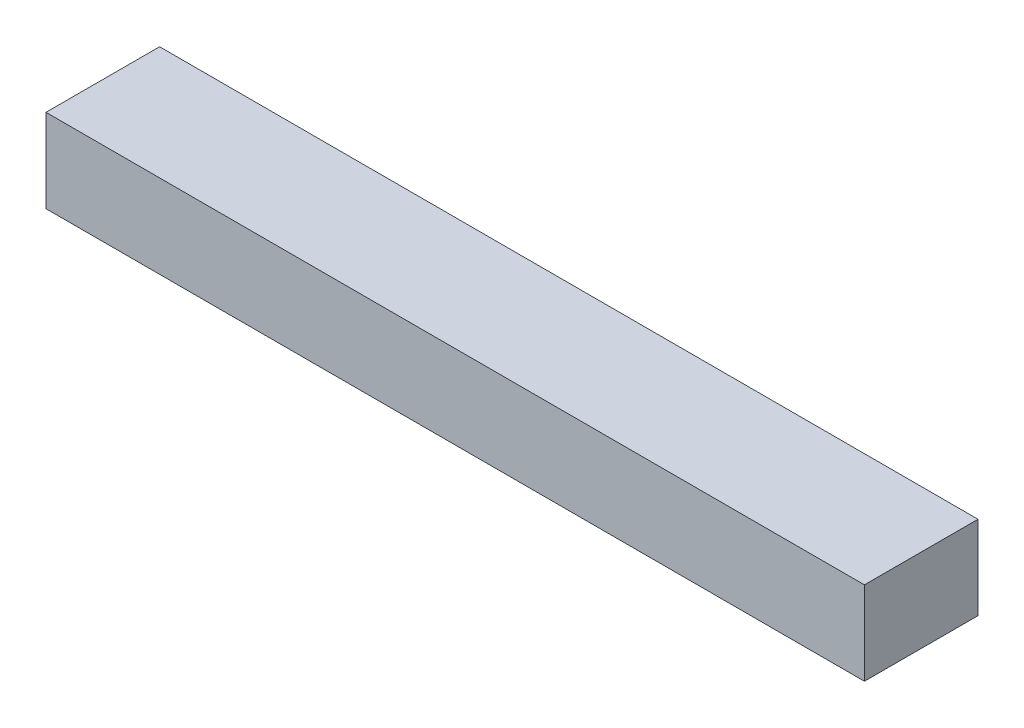
SolidWorks part; units mm, degrees
ref_plane "Front Plane" through (0, 0, 0) normal (0, 0, 1) x (1, 0, 0)
ref_plane "Top Plane" through (0, 0, 0) normal (0, 1, 0) x (1, 0, 0)
ref_plane "Right Plane" through (0, 0, 0) normal (1, 0, 0) x (0, 0, -1)
sketch "Sketch1" plane through (0, 0, 0) normal (0, 1, 0) x (1, 0, 0)
  line L1 (-23.6768, 6.5133) -> (-72.6768, 6.5133)
  line L2 (-23.6768, 6.5133) -> (-23.6768, -0.2867)
  line L3 (-23.6768, -0.2867) -> (-72.6768, -0.2867)
  line L4 (-72.6768, 6.5133) -> (-72.6768, -0.2867)
  dimension "D1" = 49
  dimension "D2" = 6.8
extrude "Boss-Extrude1" add sketch "Sketch1" along normal blind 5
